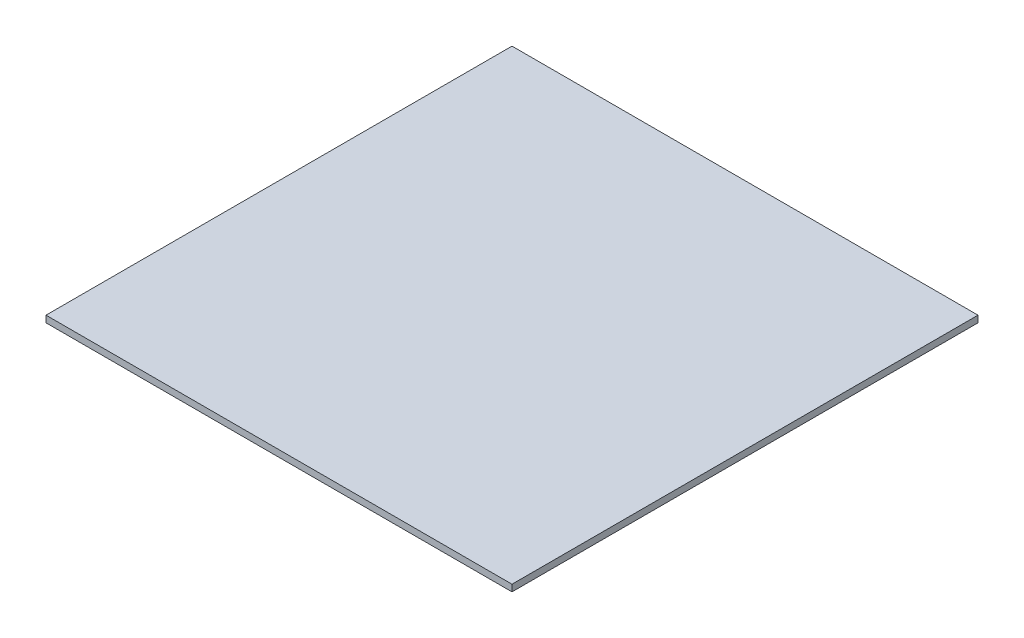
SolidWorks part; units mm, degrees
ref_plane "Front Plane" through (0, 0, 0) normal (0, 0, 1) x (1, 0, 0)
ref_plane "Top Plane" through (0, 0, 0) normal (0, 1, 0) x (1, 0, 0)
ref_plane "Right Plane" through (0, 0, 0) normal (1, 0, 0) x (0, 0, -1)
sketch "Sketch1" plane through (0, 0, 0) normal (0, 1, 0) x (1, 0, 0)
  line L0 (103.5653, -42.9983) -> (103.5653, 237.0017) construction
  line L1 (-36.4347, 237.0017) -> (243.5653, 237.0017)
  line L2 (-36.4347, 237.0017) -> (-36.4347, -42.9983)
  line L3 (-36.4347, -42.9983) -> (243.5653, -42.9983)
  line L4 (243.5653, 237.0017) -> (243.5653, -42.9983)
  line L5 (243.5653, 97.0017) -> (-36.4347, 97.0017) construction
extrude "Boss-Extrude1" add sketch "Sketch1" along normal blind 4
